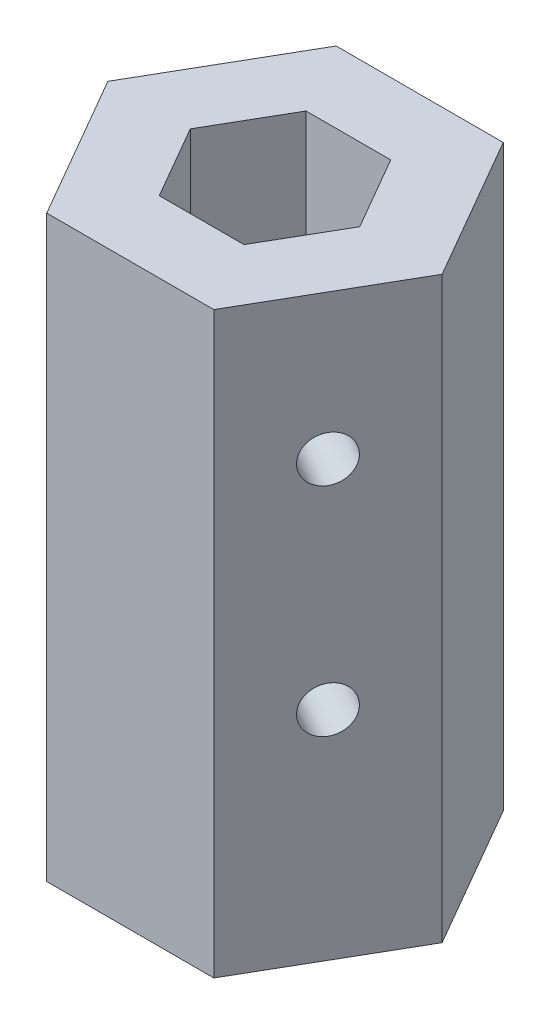
SolidWorks part; units mm, degrees
material "ABS"
ref_plane "Front Plane" through (0, 0, 0) normal (0, 0, 1) x (1, 0, 0)
ref_plane "Top Plane" through (0, 0, 0) normal (0, 1, 0) x (1, 0, 0)
ref_plane "Right Plane" through (0, 0, 0) normal (1, 0, 0) x (0, 0, -1)
sketch "Sketch1" plane through (0, 0, 0) normal (0, 1, 0) x (1, 0, 0)
  line L1 (3.7175, 6.4389) -> (-3.7175, 6.4389)
  line L2 (-3.7175, 6.4389) -> (-7.435, 0)
  line L3 (-7.435, 0) -> (-3.7175, -6.4389)
  line L4 (-3.7175, -6.4389) -> (3.7175, -6.4389)
  line L5 (3.7175, -6.4389) -> (7.435, 0)
  line L6 (7.435, 0) -> (3.7175, 6.4389)
  line L7 (7.3323, 12.7) -> (-7.3323, 12.7)
  line L8 (-7.3323, 12.7) -> (-14.6647, 0)
  line L9 (-14.6647, 0) -> (-7.3323, -12.7)
  line L10 (-7.3323, -12.7) -> (7.3323, -12.7)
  line L11 (7.3323, -12.7) -> (14.6647, 0)
  line L12 (14.6647, 0) -> (7.3323, 12.7)
  circle A0 centre (0, 0) radius 6.4389 construction
  circle A1 centre (0, 0) radius 12.7 construction
  dimension "D1" = 6.4389
  dimension "D2" = 25.4
extrude "Boss-Extrude1" add sketch "Sketch1" along normal blind 50.8
sketch "Sketch2" plane through (0, 0, 0) normal (0, -1, 0) x (1, 0, 0)
  line L0 (3.7175, -6.4389) -> (-3.7175, -6.4389) construction
  line L1 (-3.7175, -6.4389) -> (-7.435, 0) construction
  line L2 (-7.435, 0) -> (-3.7175, 6.4389) construction
  line L3 (7.435, 0) -> (3.7175, -6.4389) construction
  line L4 (3.7175, 6.4389) -> (7.435, 0) construction
  line L5 (-3.7175, 6.4389) -> (3.7175, 6.4389) construction
  line L6 (3.7175, -6.4389) -> (-3.7175, -6.4389)
  line L7 (-3.7175, -6.4389) -> (-7.435, 0)
  line L8 (-7.435, 0) -> (-3.7175, 6.4389)
  line L9 (7.435, 0) -> (3.7175, -6.4389)
  line L10 (3.7175, 6.4389) -> (7.435, 0)
  line L11 (-3.7175, 6.4389) -> (3.7175, 6.4389)
extrude "Boss-Extrude2" add sketch "Sketch2" against normal blind 6.35
sketch "Sketch3" plane through (10.9985, 0, 6.35) normal (0.866, 0, 0.5) x (0.5, 0, -0.866)
  line L0 (0, 0) -> (0, 6.35) construction
  line L1 (-7.3323, 0) -> (7.3323, 0) construction
  line L2 (0, 6.35) -> (0, 19.05) construction
  line L3 (0, 19.05) -> (0, 38.1) construction
  circle A0 centre (0, 19.05) radius 2.0193
  circle A1 centre (0, 38.1) radius 2.0193
  dimension "D3" = 4.0386
  dimension "D5" = 4.0386
  dimension "D1" = 6.35
  dimension "D2" = 12.7
  dimension "D4" = 31.75
extrude "Cut-Extrude1" cut sketch "Sketch3" against normal through all
sketch "Sketch4" plane through (-5.5763, 0, -3.2194) normal (0.866, 0, 0.5) x (0.5, 0, -0.866)
  circle A0 centre (0, 38.1) radius 2.0193 construction
  circle A1 centre (0, 38.1) radius 2.0193 construction
  circle A2 centre (0, 38.1) radius 2.6289
  circle A3 centre (0, 19.05) radius 2.6289
  dimension "D1" = 5.2578
  dimension "D2" = 5.2578
extrude "Cut-Extrude2" cut sketch "Sketch4" against normal through all
